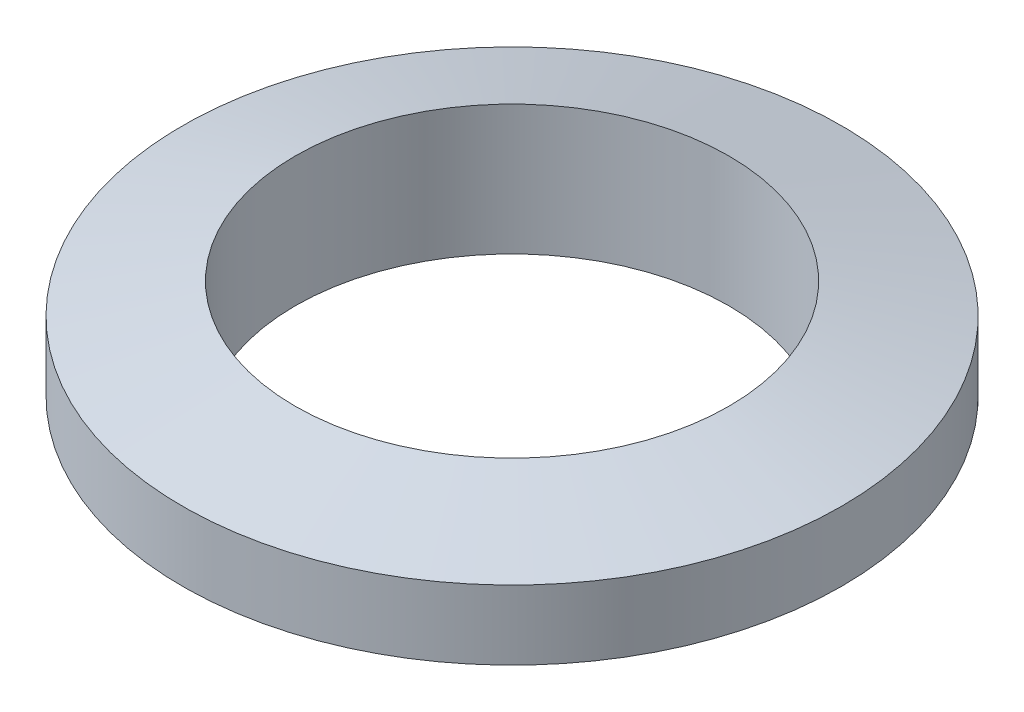
SolidWorks part; units mm, degrees
material "Эпихлоргидрин"
ref_plane "Спереди" through (0, 0, 0) normal (0, 0, 1) x (1, 0, 0)
ref_plane "Сверху" through (0, 0, 0) normal (0, 1, 0) x (1, 0, 0)
ref_plane "Справа" through (0, 0, 0) normal (1, 0, 0) x (0, 0, -1)
sketch "Эскиз1" plane through (0, 0, 0) normal (0, 0, 1) x (1, 0, 0)
  line L0 (-147.7989, 0) -> (7242.1473, 0) construction
  line L1 (0, -1000) -> (0, 49000) construction
  line L2 (-12.5, 3.7417) -> (-19, 2)
  line L3 (-19, 2) -> (-19, -2)
  line L4 (-19, -2) -> (-12.5, -3.7417)
  line L5 (-12.5, -3.7417) -> (-12.5, 3.7417)
  dimension "D1" = 30
  dimension "D2" = 19
  dimension "D3" = 12.5
  dimension "D4" = 15
  dimension "D5" = 4
  dimension "D6" = 2
revolve "Повернуть1" add sketch "Эскиз1" angle 360 about L1
